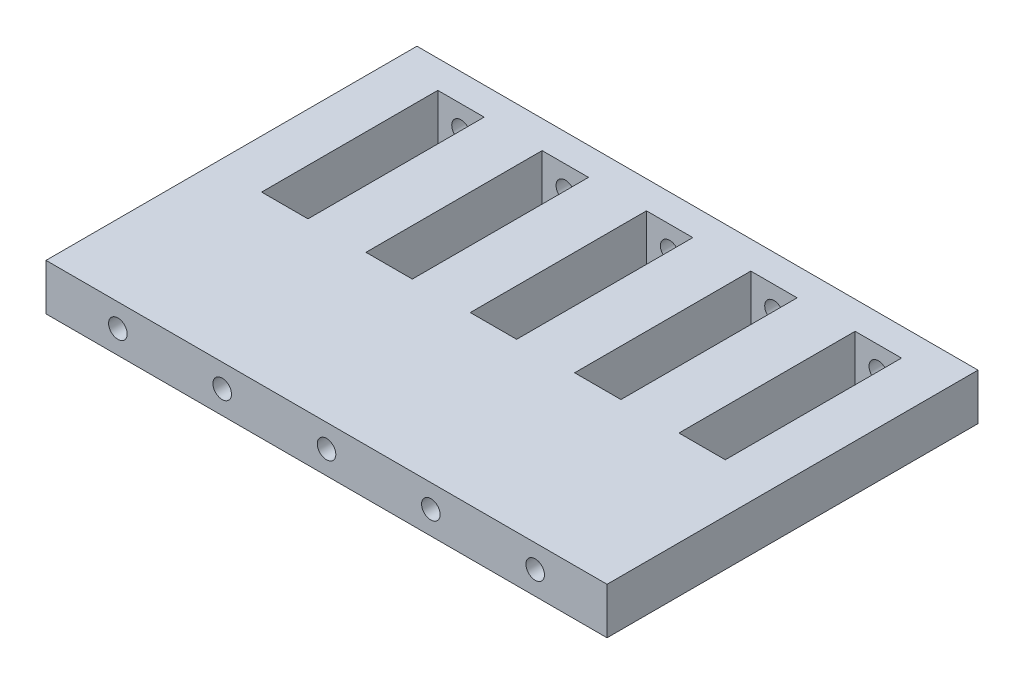
SolidWorks part; units mm, degrees
ref_plane "Front Plane" through (0, 0, 0) normal (0, 0, 1) x (1, 0, 0)
ref_plane "Top Plane" through (0, 0, 0) normal (0, 1, 0) x (1, 0, 0)
ref_plane "Right Plane" through (0, 0, 0) normal (1, 0, 0) x (0, 0, -1)
sketch "Sketch1" plane through (0, 0, 0) normal (0, 1, 0) x (1, 0, 0)
  line L0 (0, 0) -> (50.5, 0) construction
  line L1 (0, 0) -> (-50.5, 0) construction
  line L3 (-50.5, 0) -> (70.5, 0)
  line L4 (-50.5, 0) -> (-50.5, 80)
  line L5 (-50.5, 80) -> (70.5, 80)
  line L6 (70.5, 0) -> (70.5, 80)
  dimension "D1" = 50.5
  dimension "D2" = 50.5
  dimension "D3" = 80
  dimension "D4" = 121
extrude "Boss-Extrude1" add sketch "Sketch1" along normal blind 10
sketch "Sketch2" plane through (0, 10, 0) normal (0, 1, 0) x (1, 0, 0)
  line L0 (-50.5, 80) -> (-40, 80) construction
  line L1 (70.5, 80) -> (-50.5, 80) construction
  line L2 (-40, 80) -> (-40, 6) construction
  line L3 (-40, 6) -> (-30, 6) construction
  line L4 (-40, 80) -> (-40, 74) construction
  line L5 (-30, 6) -> (-16.5, 6) construction
  line L6 (-40, 74) -> (-30, 74)
  line L7 (-40, 74) -> (-40, 6)
  line L8 (-40, 6) -> (-30, 6)
  line L9 (-30, 74) -> (-30, 6)
  line L10 (-17.5, 74) -> (-17.5, 6)
  line L11 (-17.5, 74) -> (-7.5, 74)
  line L12 (-7.5, 74) -> (-7.5, 6)
  line L13 (-17.5, 6) -> (-7.5, 6)
  line L14 (5, 74) -> (5, 6)
  line L15 (5, 74) -> (15, 74)
  line L16 (15, 74) -> (15, 6)
  line L17 (5, 6) -> (15, 6)
  line L18 (27.5, 74) -> (27.5, 6)
  line L19 (27.5, 74) -> (37.5, 74)
  line L20 (37.5, 74) -> (37.5, 6)
  line L21 (27.5, 6) -> (37.5, 6)
  line L22 (50, 74) -> (50, 6)
  line L23 (50, 74) -> (60, 74)
  line L24 (60, 74) -> (60, 6)
  line L25 (50, 6) -> (60, 6)
  dimension "D1" = 10.5
  dimension "D2" = 74
  dimension "D3" = 10
  dimension "D4" = 6
  dimension "D5" = 13.5
  dimension "D6" = 5
extrude "Cut-Extrude1" cut sketch "Sketch2" against normal blind 10
sketch "Sketch7" plane through (0, 0, 0) normal (0, 0, 1) x (1, 0, 0)
  line L0 (-50.5, 5) -> (-35, 5) construction
  line L1 (-50.5, 10) -> (-50.5, 0) construction
  circle A0 centre (-35, 5) radius 2
  circle A1 centre (-12.5, 5) radius 2
  circle A2 centre (10, 5) radius 2
  circle A3 centre (32.5, 5) radius 2
  circle A4 centre (55, 5) radius 2
  dimension "D2" = 4
  dimension "D1" = 15.5
  dimension "D3" = 5
extrude "Cut-Extrude4" cut sketch "Sketch7" against normal through all
sketch "Sketch8" plane through (0, 10, 0) normal (0, 1, 0) x (1, 0, 0)
  line L6 (-40, 6) -> (60, 6)
  line L7 (-40, 6) -> (-40, 36)
  line L8 (-40, 36) -> (60, 36)
  line L9 (60, 6) -> (60, 36)
  dimension "D1" = 30
  dimension "D2" = 100
extrude "Boss-Extrude4" add sketch "Sketch8" against normal blind 10
